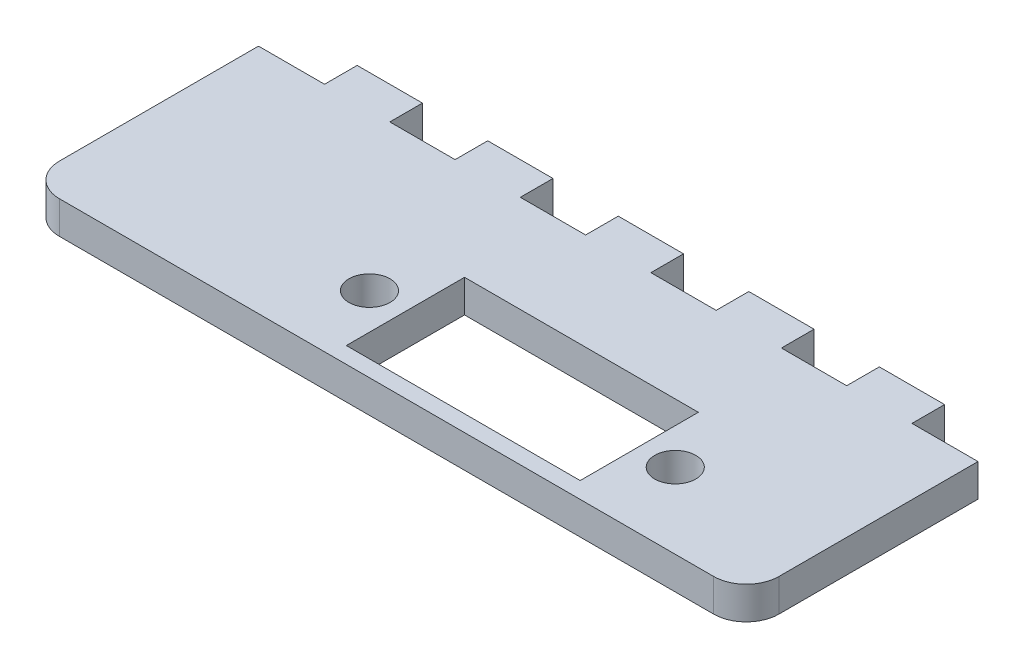
SolidWorks part; units mm, degrees
material "Acrylic (Medium-high impact)"
ref_plane "Front Plane" through (0, 0, 0) normal (0, 0, 1) x (1, 0, 0)
ref_plane "Top Plane" through (0, 0, 0) normal (0, 1, 0) x (1, 0, 0)
ref_plane "Right Plane" through (0, 0, 0) normal (1, 0, 0) x (0, 0, -1)
sketch "Sketch1" plane through (0, 0, 0) normal (0, 1, 0) x (1, 0, 0)
  line L0 (0, 11.2712) -> (70, 11.2713) construction
  line L1 (0, 0) -> (70, 0)
  line L2 (0, 0) -> (0, 22.5425)
  line L3 (0, 22.5425) -> (6.425, 22.5425)
  line L4 (70, 0) -> (70, 22.5425)
  line L5 (29.5, 1.5875) -> (52.25, 1.5875)
  line L6 (29.5, 1.5875) -> (29.5, 13.0875)
  line L7 (29.5, 13.0875) -> (52.25, 13.0875)
  line L8 (52.25, 1.5875) -> (52.25, 13.0875)
  line L9 (35, 25.7175) -> (35, 0) construction
  line L10 (38.175, 22.5425) -> (38.175, 25.7175)
  line L11 (38.175, 25.7175) -> (31.825, 25.7175)
  line L12 (31.825, 25.7175) -> (31.825, 22.5425)
  line L13 (44.525, 25.7175) -> (44.525, 22.5425)
  line L14 (50.875, 25.7175) -> (44.525, 25.7175)
  line L15 (50.875, 22.5425) -> (50.875, 25.7175)
  line L16 (57.225, 25.7175) -> (57.225, 22.5425)
  line L17 (63.575, 25.7175) -> (57.225, 25.7175)
  line L18 (63.575, 22.5425) -> (63.575, 25.7175)
  line L19 (19.125, 25.7175) -> (19.125, 22.5425)
  line L20 (25.475, 25.7175) -> (19.125, 25.7175)
  line L21 (25.475, 22.5425) -> (25.475, 25.7175)
  line L22 (6.425, 25.7175) -> (6.425, 22.5425)
  line L23 (12.775, 25.7175) -> (6.425, 25.7175)
  line L24 (12.775, 22.5425) -> (12.775, 25.7175)
  line L25 (12.775, 22.5425) -> (19.125, 22.5425)
  line L26 (25.475, 22.5425) -> (31.825, 22.5425)
  line L27 (38.175, 22.5425) -> (44.525, 22.5425)
  line L28 (50.875, 22.5425) -> (57.225, 22.5425)
  line L29 (63.575, 22.5425) -> (70, 22.5425)
  line L30 (29.5, 7.3375) -> (52.25, 7.3375) construction
  line L31 (40.875, 13.0875) -> (40.875, 1.5875) construction
  circle A0 centre (26, 7.3375) radius 2
  circle A1 centre (55.75, 7.3375) radius 2
  point P17 (35, 25.7175)
  point P21 (35, 0)
  dimension "D11" = 4
  dimension "D1" = 22.5425
  dimension "D2" = 70
  dimension "D3" = 22.75
  dimension "D4" = 11.5
  dimension "D5" = 3.175
  dimension "D6" = 6.35
  dimension "D7" = 3
  dimension "D9" = 6.35
  dimension "D10" = 6.35
  dimension "D12" = 3.5
  dimension "D13" = 1.5875
  dimension "D14" = 5.5
  dimension "D8" = 3
extrude "Boss-Extrude1" add sketch "Sketch1" along normal blind 3.175
fillet "Fillet1" radius 3.175 2 edges at (0, 1.5875, 0) (70, 1.5875, 0)
